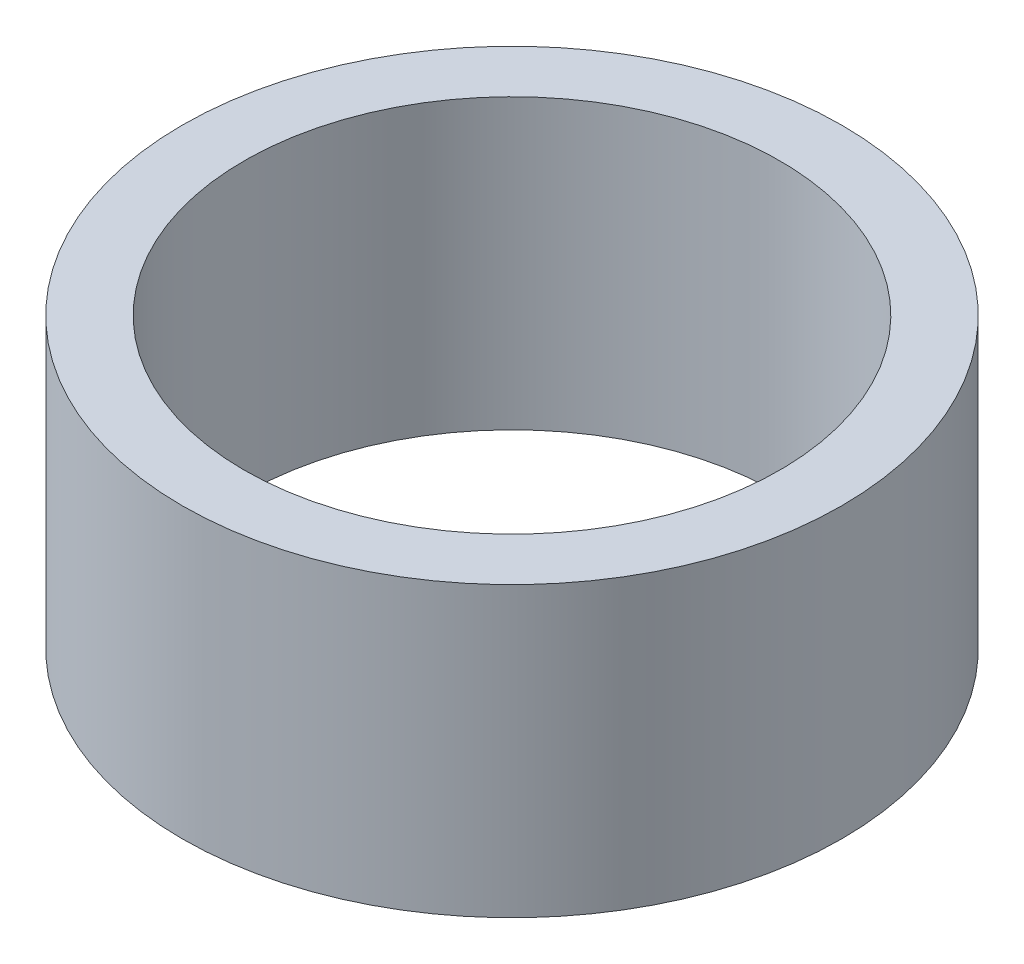
SolidWorks part; units mm, degrees
ref_plane "Ön Düzlem" through (0, 0, 0) normal (0, 0, 1) x (1, 0, 0)
ref_plane "Üst Düzlem" through (0, 0, 0) normal (0, 1, 0) x (1, 0, 0)
ref_plane "Sağ Düzlem" through (0, 0, 0) normal (1, 0, 0) x (0, 0, -1)
sketch "Çizim1" plane through (0, 0, 0) normal (0, 1, 0) x (1, 0, 0)
  circle A0 centre (0, 0) radius 13
  dimension "D1" = 26
extrude "Ekstrüzyon-İnce1" add sketch "Çizim1" along normal blind 14 thin
